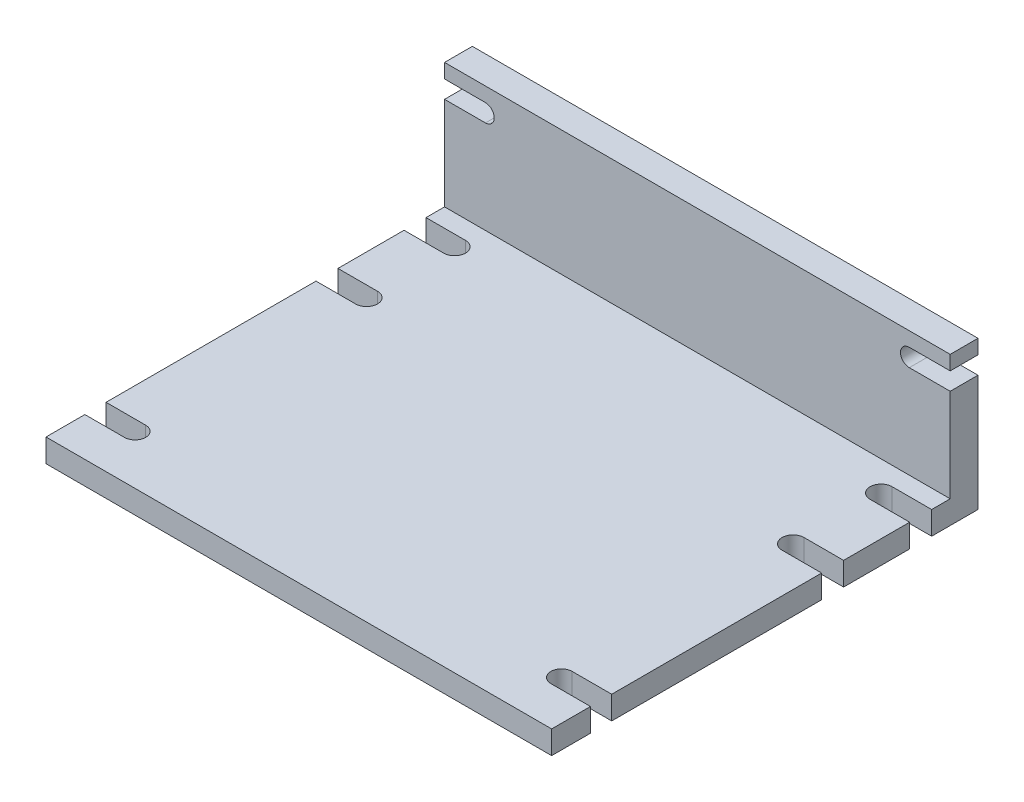
SolidWorks part; units mm, degrees
ref_plane "Alzado" through (0, 0, 0) normal (0, 0, 1) x (1, 0, 0)
ref_plane "Planta" through (0, 0, 0) normal (0, 1, 0) x (1, 0, 0)
ref_plane "Vista lateral" through (0, 0, 0) normal (1, 0, 0) x (0, 0, -1)
sketch "Croquis1" plane through (0, 0, 0) normal (0, 1, 0) x (1, 0, 0)
  line L1 (54.555, -46) -> (-54.555, -46)
  line L2 (54.555, -46) -> (54.555, 46)
  line L3 (54.555, 46) -> (-54.555, 46)
  line L4 (-54.555, -46) -> (-54.555, 46)
  line L5 (54.555, -46) -> (-54.555, 46) construction
  line L6 (54.555, 46) -> (-54.555, -46) construction
  point P0 (0, 0)
  dimension "D1" = 92
  dimension "D2" = 109.11
extrude "Saliente-Extruir1" add sketch "Croquis1" along normal blind 32
sketch "Croquis2" plane through (54.555, 0, 0) normal (1, 0, 0) x (0, 0, -1)
  line L0 (46, 32) -> (46, 0) construction
  line L1 (-46, 32) -> (40, 32)
  line L2 (-46, 32) -> (-46, 5)
  line L3 (-46, 5) -> (40, 5)
  line L4 (40, 32) -> (40, 5)
  line L5 (-46, 0) -> (46, 0) construction
  dimension "D1" = 6
  dimension "D2" = 5
extrude "Cortar-Extruir1" cut sketch "Croquis2" against normal through all
sketch "Croquis3" plane through (0, 0, -40) normal (0, 0, 1) x (1, 0, 0)
  line L0 (-54.555, 32) -> (54.555, 32) construction
  line L1 (54.555, 5) -> (54.555, 32) construction
  line L2 (45.735, 28.9) -> (54.555, 28.9)
  line L3 (54.555, 28.9) -> (54.555, 25.1)
  line L4 (54.555, 25.1) -> (45.735, 25.1)
  line L5 (0, 0) -> (0, 32) construction
  line L6 (-45.735, 28.9) -> (-54.555, 28.9)
  line L7 (-54.555, 28.9) -> (-54.555, 25.1)
  line L8 (-54.555, 25.1) -> (-45.735, 25.1)
  arc A0 (45.735, 28.9) -> (45.735, 25.1) centre (45.735, 27) ccw
  arc A1 (-45.735, 28.9) -> (-45.735, 25.1) centre (-45.735, 27) cw
  dimension "D1" = 3.8
  dimension "D2" = 5
  dimension "D3" = 8.82
extrude "Cortar-Extruir2" cut sketch "Croquis3" against normal through all
sketch "Croquis4" plane through (0, 5, 0) normal (0, 1, 0) x (1, 0, 0)
  line L0 (-46.015, 36) -> (-54.555, 36)
  line L1 (-54.555, -46) -> (-54.555, 40) construction
  line L2 (-54.555, 36) -> (-54.555, 31.26)
  line L3 (-54.555, 31.26) -> (-46.015, 31.26)
  line L4 (54.555, 46) -> (-54.555, 46) construction
  line L5 (-54.555, 14.63) -> (54.555, 14.63) construction
  line L6 (54.555, -46) -> (54.555, 40) construction
  line L7 (-46.015, 17) -> (-54.555, 17)
  line L8 (-54.555, 17) -> (-54.555, 12.26)
  line L9 (-54.555, 12.26) -> (-46.015, 12.26)
  line L10 (-46.015, -33.0379) -> (-54.555, -33.0379)
  line L11 (-54.555, -33.0379) -> (-54.555, -37.6156)
  line L12 (-54.555, -37.6156) -> (-46.015, -37.6156)
  line L13 (-54.555, -46) -> (54.555, -46) construction
  line L14 (0, -46) -> (0, 46) construction
  line L15 (54.555, -37.6156) -> (46.015, -37.6156)
  line L16 (54.555, -33.0379) -> (54.555, -37.6156)
  line L17 (46.015, -33.0379) -> (54.555, -33.0379)
  line L18 (54.555, 17) -> (54.555, 12.26)
  line L19 (46.015, 17) -> (54.555, 17)
  line L20 (54.555, 12.26) -> (46.015, 12.26)
  line L21 (54.555, 31.26) -> (46.015, 31.26)
  line L22 (54.555, 36) -> (54.555, 31.26)
  line L23 (46.015, 36) -> (54.555, 36)
  arc A0 (-46.015, 31.26) -> (-46.015, 36) centre (-46.015, 33.63) ccw
  arc A1 (-46.015, 12.26) -> (-46.015, 17) centre (-46.015, 14.63) ccw
  arc A2 (-46.015, -37.6156) -> (-46.015, -33.0379) centre (-46.015, -35.3267) ccw
  arc A3 (46.015, -37.6156) -> (46.015, -33.0379) centre (46.015, -35.3267) cw
  arc A4 (46.015, 12.26) -> (46.015, 17) centre (46.015, 14.63) cw
  arc A5 (46.015, 31.26) -> (46.015, 36) centre (46.015, 33.63) cw
  point P17 (-50.285, 12.26)
  dimension "D1" = 4.74
  dimension "D5" = 4.74
  dimension "D2" = 8.54
  dimension "D3" = 10
  dimension "D4" = 14.26
  dimension "D6" = 14
extrude "Cortar-Extruir4" cut sketch "Croquis4" against normal through all
